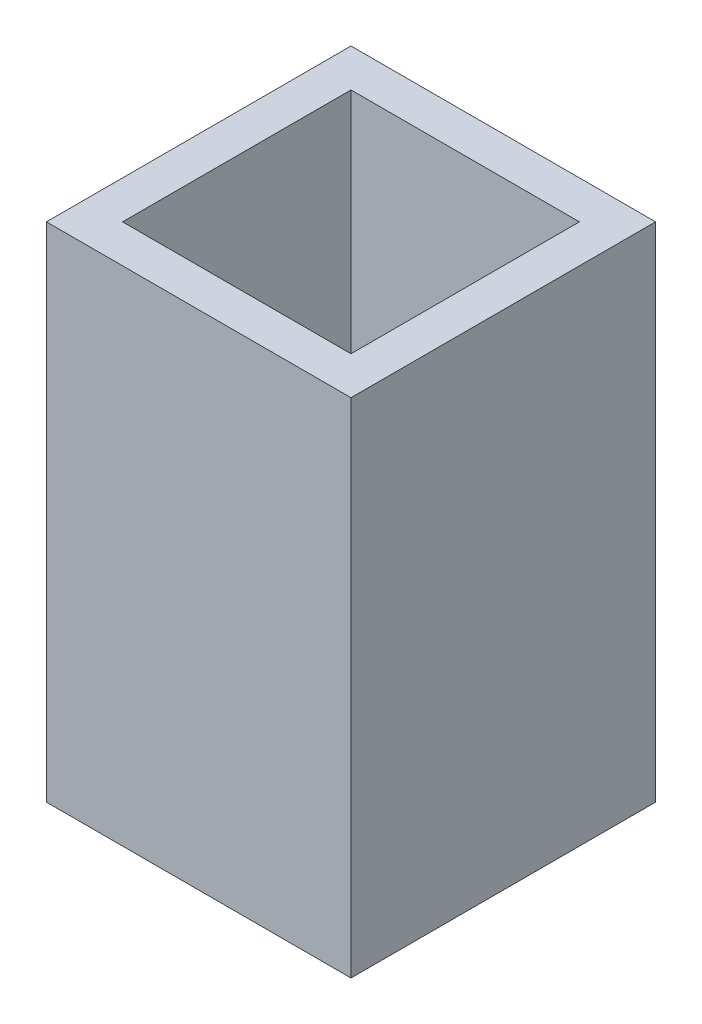
SolidWorks part; units mm, degrees
ref_plane "Front Plane" through (0, 0, 0) normal (0, 0, 1) x (1, 0, 0)
ref_plane "Top Plane" through (0, 0, 0) normal (0, 1, 0) x (1, 0, 0)
ref_plane "Right Plane" through (0, 0, 0) normal (1, 0, 0) x (0, 0, -1)
sketch "Sketch1" plane through (0, 0, 0) normal (0, 1, 0) x (1, 0, 0)
  line L1 (0, 0) -> (25.4, 0)
  line L2 (0, 0) -> (0, 25.4)
  line L3 (0, 25.4) -> (25.4, 25.4)
  line L4 (25.4, 0) -> (25.4, 25.4)
  dimension "D1" = 25.4
  dimension "D2" = 25.4
extrude "Boss-Extrude1" add sketch "Sketch1" along normal blind 41.91
sketch "Sketch4" plane through (0, 0, 0) normal (0, -1, 0) x (-1, 0, 0)
  line L0 (-25.4, 25.4) -> (0, 25.4) construction
  line L1 (-22.225, 3.175) -> (-3.175, 3.175)
  line L2 (-22.225, 3.175) -> (-22.225, 22.225)
  line L3 (-22.225, 22.225) -> (-3.175, 22.225)
  line L4 (-3.175, 3.175) -> (-3.175, 22.225)
  line L5 (0, 25.4) -> (0, 0) construction
  line L6 (0, 0) -> (-25.4, 0) construction
  line L7 (-25.4, 0) -> (-25.4, 25.4) construction
  dimension "D1" = 3.175
  dimension "D2" = 3.175
  dimension "D3" = 3.175
  dimension "D4" = 3.175
extrude "Cut-Extrude2" cut sketch "Sketch4" against normal through all
